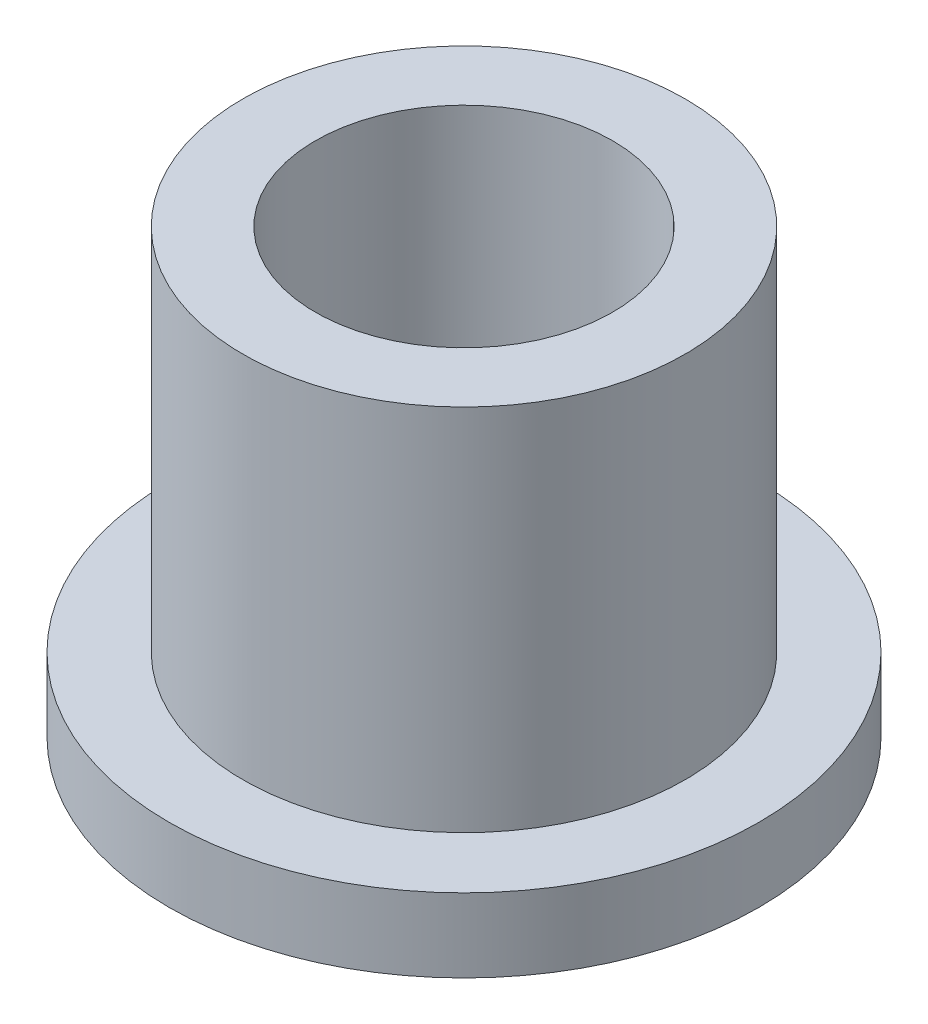
SolidWorks part; units mm, degrees
ref_plane "Front" through (0, 0, 0) normal (0, 0, 1) x (1, 0, 0)
ref_plane "Top" through (0, 0, 0) normal (0, 1, 0) x (1, 0, 0)
ref_plane "Right" through (0, 0, 0) normal (1, 0, 0) x (0, 0, -1)
sketch "Sketch1" plane through (0, 0, 0) normal (0, 1, 0) x (1, 0, 0)
  circle A0 centre (0, 0) radius 6.4008
  circle A1 centre (0, 0) radius 9.525
  circle A2 centre (0, 0) radius 12.7
  dimension "ID" = 12.8016
  dimension "OD" = 19.05
  dimension "FlangeOD" = 25.4
sketch "Sketch2" plane through (0, 0, 0) normal (0, 1, 0) x (1, 0, 0)
  circle A0 centre (0, 0) radius 6.4008 construction
  circle A1 centre (0, 0) radius 9.525 construction
  circle A2 centre (0, 0) radius 6.4008
  circle A3 centre (0, 0) radius 9.525
extrude "Boss-Extrude1" add sketch "Sketch2" along normal blind 19.05
sketch "Sketch3" plane through (0, 0, 0) normal (0, 1, 0) x (1, 0, 0)
  circle A0 centre (0, 0) radius 12.7 construction
  circle A1 centre (0, 0) radius 9.525 construction
  circle A2 centre (0, 0) radius 12.7
  circle A3 centre (0, 0) radius 9.525
extrude "Boss-Extrude2" add sketch "Sketch3" along normal blind 3.175
